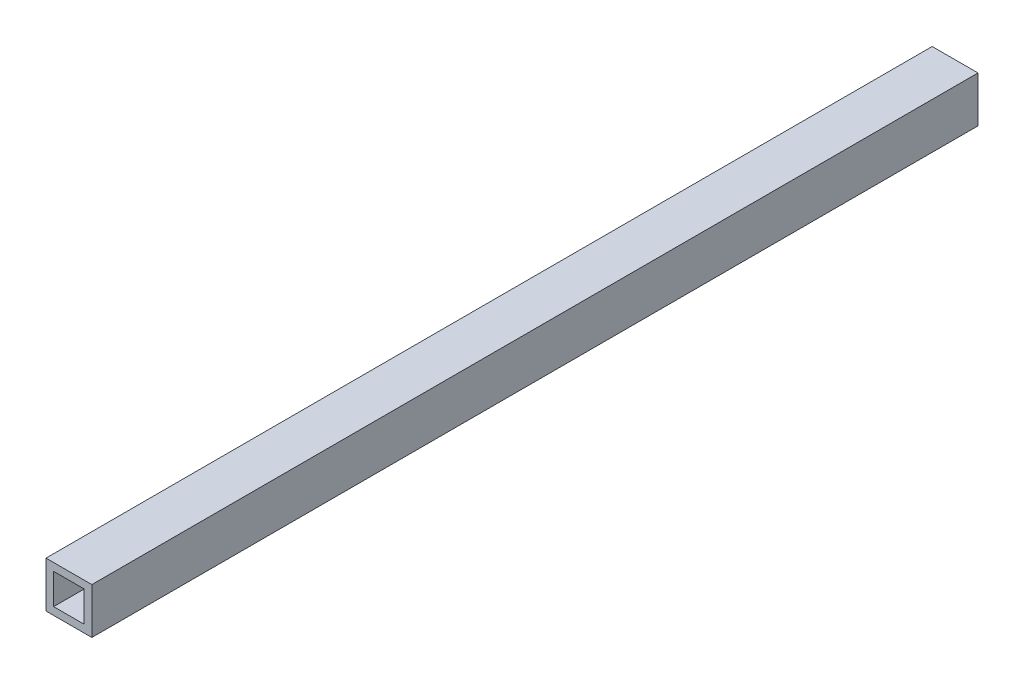
SolidWorks part; units mm, degrees
material "6061-T6 (SS)"
ref_plane "Front Plane" through (0, 0, 0) normal (0, 0, 1) x (1, 0, 0)
ref_plane "Top Plane" through (0, 0, 0) normal (0, 1, 0) x (1, 0, 0)
ref_plane "Right Plane" through (0, 0, 0) normal (1, 0, 0) x (0, 0, -1)
sketch "Sketch1" plane through (0, 0, 0) normal (0, 0, 1) x (1, 0, 0)
  line L1 (-9.525, -9.525) -> (9.525, -9.525)
  line L2 (-9.525, -9.525) -> (-9.525, 9.525)
  line L3 (-9.525, 9.525) -> (9.525, 9.525)
  line L4 (9.525, -9.525) -> (9.525, 9.525)
  line L5 (-9.525, -9.525) -> (9.525, 9.525) construction
  line L6 (-9.525, 9.525) -> (9.525, -9.525) construction
  line L7 (-6.35, -6.35) -> (6.35, -6.35)
  line L8 (-6.35, -6.35) -> (-6.35, 6.35)
  line L9 (-6.35, 6.35) -> (6.35, 6.35)
  line L10 (6.35, -6.35) -> (6.35, 6.35)
  line L11 (-6.35, -6.35) -> (6.35, 6.35) construction
  line L12 (-6.35, 6.35) -> (6.35, -6.35) construction
  point P0 (0, 0)
  point P5 (0, 0)
  dimension "D1" = 19.05
  dimension "D2" = 3.175
extrude "Boss-Extrude1" add sketch "Sketch1" along normal mid plane 368.3
